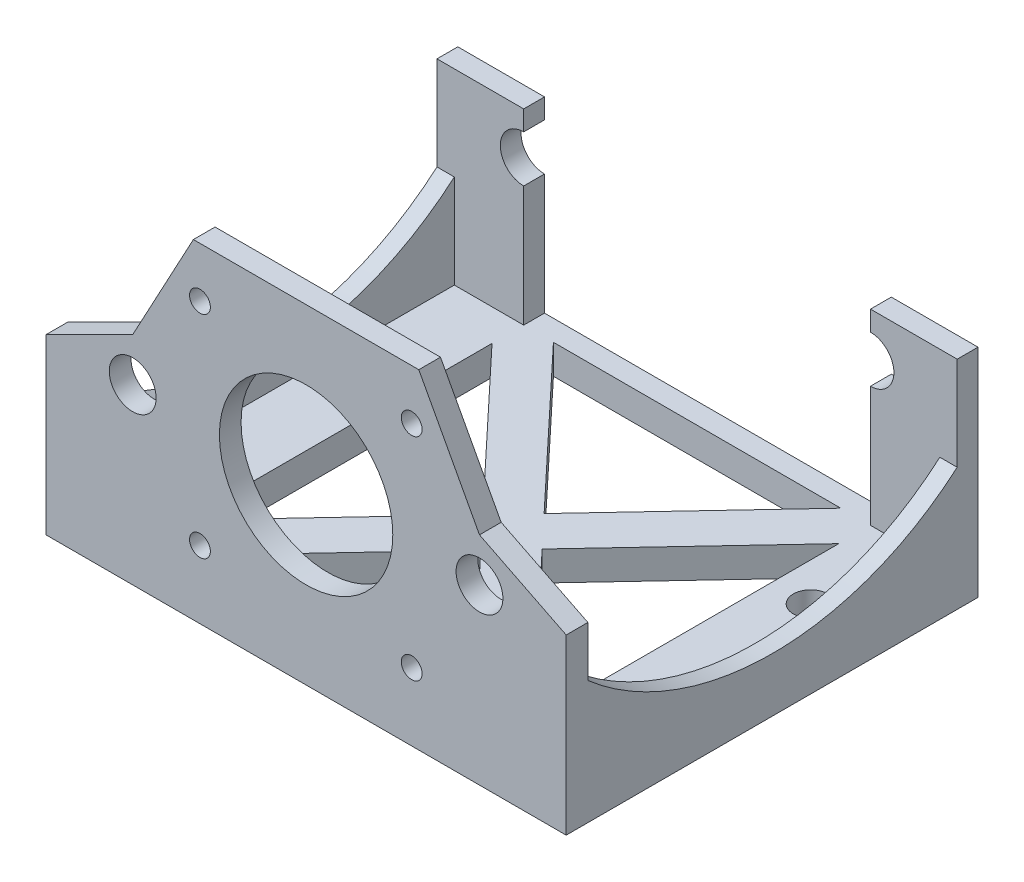
SolidWorks part; units mm, degrees
ref_plane "Front Plane" through (0, 0, 0) normal (0, 0, 1) x (1, 0, 0)
ref_plane "Top Plane" through (0, 0, 0) normal (0, 1, 0) x (1, 0, 0)
ref_plane "Right Plane" through (0, 0, 0) normal (1, 0, 0) x (0, 0, -1)
sketch "Sketch1" plane through (0, 0, 0) normal (0, 0, 1) x (1, 0, 0)
  line L0 (31.75, 25.4) -> (25.4, 25.4)
  line L1 (-31.75, 25.4) -> (-38.1, 0)
  line L2 (-38.1, 0) -> (-38.1, -25.4)
  line L3 (-38.1, -25.4) -> (38.1, -25.4)
  line L4 (38.1, -25.4) -> (38.1, 0)
  line L5 (38.1, 0) -> (31.75, 25.4)
  line L6 (0, 0) -> (0, -25.4) construction
  line L7 (0, 0) -> (0, 25.4) construction
  line L8 (-25.4, 0) -> (25.4, 0) construction
  line L9 (-25.4, 25.4) -> (-25.4, 22.86)
  line L10 (-25.4, 22.86) -> (25.4, 22.86)
  line L11 (25.4, 22.86) -> (25.4, 25.4)
  line L12 (-25.4, 25.4) -> (-31.75, 25.4)
  circle A0 centre (-15.5448, 15.5186) radius 1.27 construction
  circle A1 centre (15.4686, 15.5186) radius 1.27 construction
  circle A2 centre (15.4686, -15.4678) radius 1.27 construction
  circle A3 centre (-15.5448, -15.4678) radius 1.27 construction
  circle A4 centre (-15.5448, 15.5186) radius 1.27
  circle A5 centre (15.4686, 15.5186) radius 1.27
  circle A6 centre (15.4686, -15.4678) radius 1.27
  circle A7 centre (-15.5448, -15.4678) radius 1.27
  circle A8 centre (0, 0) radius 9.525
  circle A9 centre (-25.4, 0) radius 3.175
  circle A10 centre (25.4, 0) radius 3.175
  dimension "D5" = 19.05
  dimension "D6" = 6.35
  dimension "D1" = 76.2
  dimension "D2" = 63.5
  dimension "D3" = 25.4
  dimension "D4" = 25.4
  dimension "D7" = 25.4
  dimension "D8" = 6.35
  dimension "D9" = 2.54
  dimension "D10" = 6.35
extrude "Boss-Extrude1" add sketch "Sketch1" along normal blind 3.175
sketch "Sketch2" plane through (0, 0, 0) normal (0, 0, -1) x (-1, 0, 0)
  line L0 (-25.4, 22.86) -> (-32.385, 22.86)
  line L1 (-38.1, 0) -> (-31.75, 25.4) construction
  line L2 (-32.385, 22.86) -> (-31.75, 25.4)
  line L3 (-31.75, 25.4) -> (-25.4, 25.4)
  line L4 (-25.4, 25.4) -> (-25.4, 22.86)
  line L5 (25.4, 22.86) -> (25.4, 25.4)
  line L6 (25.4, 25.4) -> (31.75, 25.4)
  line L7 (31.75, 25.4) -> (32.385, 22.86)
  line L8 (31.75, 25.4) -> (38.1, 0) construction
  line L9 (32.385, 22.86) -> (25.4, 22.86)
  line L10 (38.1, 0) -> (38.1, -25.4) construction
  line L11 (-38.1, -25.4) -> (38.1, -25.4)
  line L12 (-38.1, -25.4) -> (-38.1, -21.082)
  line L13 (-38.1, -21.082) -> (38.1, -21.082)
  line L14 (38.1, -25.4) -> (38.1, -21.082)
  line L15 (-32.385, 22.86) -> (-34.925, 12.7)
  line L16 (-34.925, 12.7) -> (-31.4325, 12.7)
  line L17 (-31.4325, 12.7) -> (-28.8925, 22.86)
  line L18 (0, 0) -> (0, -21.082) construction
  line L19 (31.4325, 12.7) -> (28.8925, 22.86)
  line L20 (34.925, 12.7) -> (31.4325, 12.7)
  line L21 (32.385, 22.86) -> (34.925, 12.7)
  line L22 (-31.4325, 12.7) -> (-25.4, 12.7)
  line L23 (-25.4, 12.7) -> (-25.4, 22.86)
  line L24 (25.4, 22.86) -> (25.4, 12.7)
  line L25 (25.4, 12.7) -> (31.4325, 12.7)
  line M5 (-38.1, 0) -> (-38.1, -25.4)
  line M6 (-38.1, -25.4) -> (38.1, -25.4)
  line M7 (38.1, -25.4) -> (38.1, 0)
  dimension "D1" = 4.318
extrude "Boss-Extrude2" add sketch "Sketch2" along normal blind 54.102 contours L13 M5 M6 M7
sketch "Sketch3" plane through (0, 0, -54.102) normal (0, 0, -1) x (-1, 0, 0)
  line L2 (-38.1, 6.35) -> (-25.4, 6.35)
  line L3 (-25.4, 6.35) -> (-25.4, 3.175)
  line L4 (38.1, 6.35) -> (25.4, 6.35)
  line L5 (25.4, 6.35) -> (25.4, 3.175)
  line L8 (-25.4, -3.175) -> (-25.4, -21.082)
  line L9 (-38.1, -21.082) -> (38.1, -21.082) construction
  line L10 (-25.4, -21.082) -> (25.4, -21.082)
  line L11 (25.4, -21.082) -> (25.4, -3.175)
  line L13 (-38.1, 6.35) -> (-38.1, -25.4)
  line L14 (-38.1, -25.4) -> (38.1, -25.4)
  line L15 (38.1, -25.4) -> (38.1, 6.35)
  circle A0 centre (-25.4, 0) radius 3.175 construction
  circle A1 centre (25.4, 0) radius 3.175 construction
  circle A2 centre (-25.4, 0) radius 3.175
  circle A3 centre (25.4, 0) radius 3.175
  dimension "D1" = 3.175
  dimension "D2" = 3.175
extrude "Boss-Extrude3" add sketch "Sketch3" along normal blind 3.048
sketch "Sketch10" plane through (38.1, 0, 0) normal (1, 0, 0) x (0, 0, -1)
  line L0 (0, -21.082) -> (0, 0) construction
  line L1 (0, -7.366) -> (54.102, -7.366)
  line L2 (0, -7.366) -> (0, -21.082)
  line L3 (0, -21.082) -> (54.102, -21.082)
  line L4 (54.102, -7.366) -> (54.102, -21.082)
  line L5 (54.102, 6.35) -> (54.102, -21.082) construction
extrude "Boss-Extrude7" add sketch "Sketch10" against normal blind 2.54
mirror "Mirror4" about plane through (0, 0, 0) normal (1, 0, 0) of "Boss-Extrude7"
sketch "Sketch5" plane through (0, 0, 3.175) normal (0, 0, 1) x (1, 0, 0)
  line L20 (37.846, -0.0313) -> (31.5517, 25.146)
  line L21 (31.5517, 25.146) -> (25.654, 25.146)
  line L22 (25.654, 25.146) -> (25.654, 22.606)
  line L23 (25.654, 22.606) -> (-25.654, 22.606)
  line L24 (-25.654, 22.606) -> (-25.654, 25.146)
  line L25 (-25.654, 25.146) -> (-31.5517, 25.146)
  line L26 (-31.5517, 25.146) -> (-37.846, -0.0313)
  line L27 (-37.846, -0.0313) -> (-37.846, -25.146)
  line L28 (-37.846, -25.146) -> (37.846, -25.146)
  line L29 (37.846, -25.146) -> (37.846, -0.0313)
  line L30 (37.846, -0.0313) -> (31.5517, 25.146)
  line L31 (31.5517, 25.146) -> (25.654, 25.146)
  line L32 (25.654, 25.146) -> (25.654, 22.606)
  line L33 (25.654, 22.606) -> (-25.654, 22.606)
  line L34 (-25.654, 22.606) -> (-25.654, 25.146)
  line L35 (-25.654, 25.146) -> (-31.5517, 25.146)
  line L36 (-31.5517, 25.146) -> (-37.846, -0.0313)
  line L37 (-37.846, -0.0313) -> (-37.846, -25.146)
  line L38 (-37.846, -25.146) -> (37.846, -25.146)
  line L39 (37.846, -25.146) -> (37.846, -0.0313)
  circle A0 centre (-25.4, 0) radius 3.429
  circle A3 centre (0, 0) radius 9.779
  circle A4 centre (0, 0) radius 9.779
  circle A6 centre (25.4, 0) radius 3.429
  circle A7 centre (25.4, 0) radius 3.429
  circle A9 centre (15.4686, 15.5186) radius 1.524
  circle A10 centre (15.4686, 15.5186) radius 1.524
  circle A12 centre (-15.5448, 15.5186) radius 1.524
  circle A13 centre (-15.5448, 15.5186) radius 1.524
  circle A15 centre (-15.5448, -15.4678) radius 1.524
  circle A16 centre (-15.5448, -15.4678) radius 1.524
  circle A18 centre (15.4686, -15.4678) radius 1.524
  circle A19 centre (15.4686, -15.4678) radius 1.524
  circle M17 centre (-25.4, 0) radius 3.175
  circle M18 centre (-15.5448, -15.4678) radius 1.27
  circle M19 centre (15.4686, 15.5186) radius 1.27
  circle M30 centre (-15.5448, 15.5186) radius 1.27
  circle M31 centre (15.4686, -15.4678) radius 1.27
  circle M32 centre (0, 0) radius 9.525
  circle M33 centre (25.4, 0) radius 3.175
  dimension "D1" = 6.858
  dimension "D2" = 0.254
  dimension "D3" = 0.254
  dimension "D4" = 0.254
  dimension "D5" = 0.254
  dimension "D6" = 0.254
  dimension "D7" = 0.254
  dimension "D8" = 0.254
extrude "Cut-Extrude2" cut sketch "Sketch5" against normal through all contours A0 M17 | A13 M30 | A10 M19 | A4 M32 | A7 M33 | A19 M31 | A16 M18
sketch "Sketch6" plane through (0, -21.082, 0) normal (0, 1, 0) x (1, 0, 0)
  line L0 (35.56, 0) -> (-35.56, 0) construction
  line L1 (-25.4, 54.102) -> (25.4, 54.102)
  line L2 (-25.4, 54.102) -> (-25.4, 0)
  line L3 (-25.4, 0) -> (25.4, 0)
  line L4 (25.4, 54.102) -> (25.4, 0)
  line L5 (25.4, 54.102) -> (-25.4, 0)
  line L6 (-25.4, 0) -> (-25.3362, -0.0175)
  line L7 (-25.4, 54.102) -> (25.4, 0)
  line L8 (-25.4, 49.4636) -> (21.0447, 0)
  line L9 (21.0447, 54.102) -> (-25.4, 4.6384)
  line L10 (-21.0447, 54.102) -> (25.4, 4.6384)
  line L11 (25.4, 49.4636) -> (-21.0447, 0)
  line L12 (-23.0854, 56.2753) -> (27.7146, 2.1733) construction
  line L13 (-27.7146, 51.9287) -> (23.0854, -2.1733) construction
  line L14 (27.7146, 51.9287) -> (-23.0854, -2.1733) construction
  line L15 (23.0854, 56.2753) -> (-27.7146, 2.1733) construction
  dimension "D1" = 3.175
  dimension "D2" = 3.175
extrude "Cut-Extrude3" cut sketch "Sketch6" against normal through all contours L1 L10 L9 | L9 L8 L2 | L4 L11 L10 | L8 L11 L3
sketch "Sketch7" plane through (0, 0, 3.175) normal (0, 0, 1) x (1, 0, 0)
  circle A0 centre (0, 0) radius 12.7
  dimension "D1" = 25.4
extrude "Cut-Extrude4" cut sketch "Sketch7" against normal through all
sketch "Sketch11" plane through (38.1, 0, 0) normal (1, 0, 0) x (0, 0, -1)
  line L0 (0, -7.366) -> (54.102, -7.366)
  line L1 (54.102, 6.35) -> (54.102, -7.366) construction
  line L2 (54.102, -7.366) -> (0, -7.366) construction
  arc A0 (0, -7.366) -> (54.102, -7.366) centre (27.051, 23.822) ccw
extrude "Cut-Extrude5" cut sketch "Sketch11" against normal through all
sketch "Sketch12" plane through (0, 0, 0) normal (0, 0, -1) x (-1, 0, 0)
  line L3 (-16.51, 22.86) -> (-25.4, 6.35)
  line L4 (-25.4, 22.86) -> (25.4, 22.86) construction
  line L5 (-25.4, 6.35) -> (-38.1, 0)
  line L6 (16.51, 22.86) -> (25.4, 6.35)
  line L7 (25.4, 6.35) -> (38.1, 0)
  dimension "D1" = 8.89
  dimension "D2" = 8.89
extrude "Cut-Extrude6" cut sketch "Sketch12" against normal up to next
sketch "Sketch15" plane through (0, -21.082, 0) normal (0, 1, 0) x (1, 0, 0)
  line L0 (25.4, 54.102) -> (25.4, 0) construction
  line L1 (35.56, 0) -> (21.0447, 0) construction
  line L2 (-25.4, 54.102) -> (-25.4, 0) construction
  line L4 (-35.56, 0) -> (-35.56, 54.102) construction
  line L5 (-30.988, 39.751) -> (-30.988, 14.351) construction
  line L6 (-30.988, 27.051) -> (0, 27.051) construction
  line L8 (0, 54.102) -> (0, 0) construction
  line L9 (-21.0447, 54.102) -> (21.0447, 54.102) construction
  line L10 (30.988, 27.051) -> (0, 27.051) construction
  line L11 (30.988, 39.751) -> (30.988, 14.351) construction
  line L12 (-16.51, 0) -> (-25.4, 0) construction
  line L13 (-25.4, -3.175) -> (-25.4, 0) construction
  circle A0 centre (-30.988, 39.751) radius 4.572 construction
  circle A1 centre (-30.988, 14.351) radius 4.572 construction
  circle A2 centre (-30.988, 39.751) radius 2.54
  circle A3 centre (-30.988, 14.351) radius 2.54
  circle A4 centre (30.988, 14.351) radius 4.572 construction
  circle A5 centre (30.988, 39.751) radius 4.572 construction
  circle A6 centre (30.988, 14.351) radius 2.54
  circle A7 centre (30.988, 39.751) radius 2.54
  dimension "D1" = 9.144
  dimension "D3" = 5.08
  dimension "D4" = 5.08
  dimension "D2" = 25.4
extrude "Cut-Extrude7" cut sketch "Sketch15" against normal through all
sketch "Sketch16" plane through (0, 0, 0) normal (0, 0, -1) x (-1, 0, 0)
  circle B0 centre (-25.4, 0) radius 3.429
  circle B1 centre (-15.4686, 15.5186) radius 1.524
  circle B2 centre (0, 0) radius 12.7
  circle B3 centre (15.5448, 15.5186) radius 1.524
  circle B4 centre (25.4, 0) radius 3.429
  circle B5 centre (15.5448, -15.4678) radius 1.524
  circle B6 centre (-15.4686, -15.4678) radius 1.524
sketch_block_instance "Block1-1"
sketch_block "Block1"
